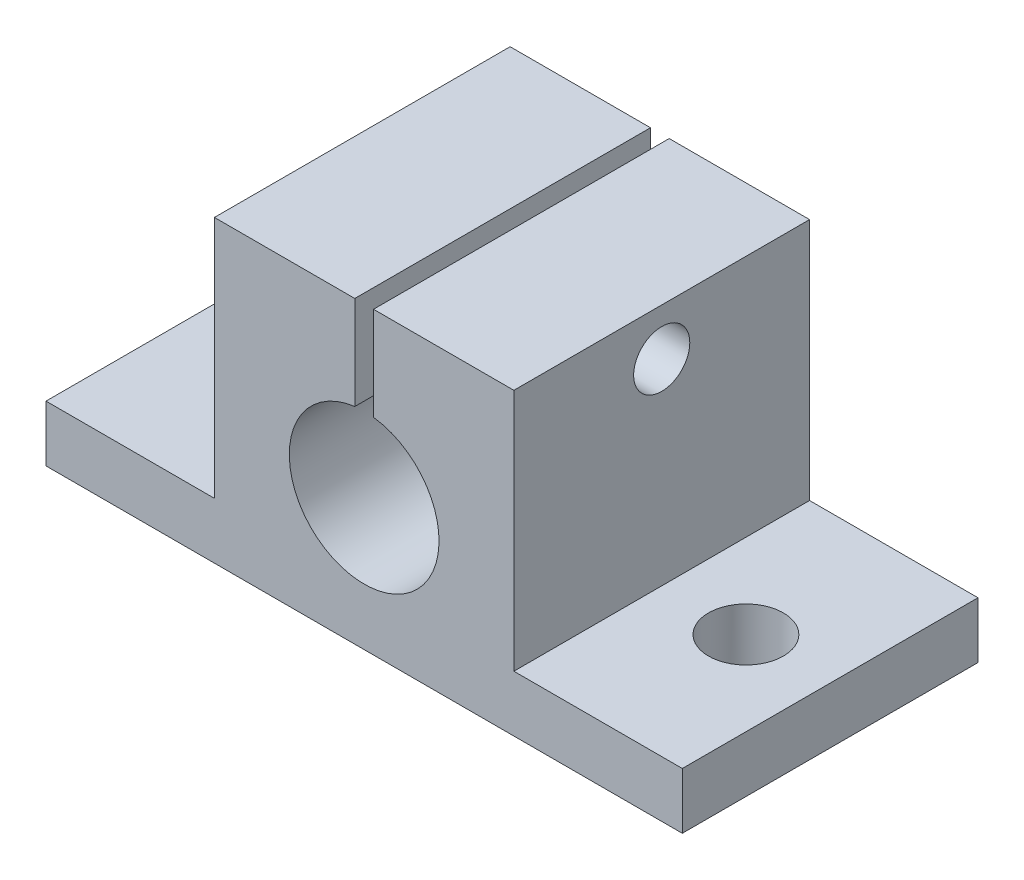
SolidWorks part; units mm, degrees
ref_plane "Front Plane" through (0, 0, 0) normal (0, 0, 1) x (1, 0, 0)
ref_plane "Top Plane" through (0, 0, 0) normal (0, 1, 0) x (1, 0, 0)
ref_plane "Right Plane" through (0, 0, 0) normal (1, 0, 0) x (0, 0, -1)
sketch "Sketch1" plane through (0, 0, 0) normal (0, 0, 1) x (1, 0, 0)
  line L0 (0, 0) -> (34, 0)
  line L1 (0, 0) -> (0, 3)
  line L2 (0, 3) -> (9, 3)
  line L3 (9, 3) -> (9, 16)
  line L4 (9, 16) -> (16.5, 16)
  line L5 (25, 16) -> (25, 3)
  line L6 (25, 3) -> (34, 3)
  line L7 (34, 3) -> (34, 0)
  line L8 (25, 16) -> (17.5, 16)
  line L9 (16.5, 16) -> (16.5, 11)
  line L10 (17.5, 16) -> (17.5, 11)
  arc A0 (17.5, 11) -> (16.5, 11) centre (17, 7.0314) cw
  point P11 (0, 0)
  point P12 (17, 0)
  point P16 (17, 3.0314)
  dimension "D8" = 4
  dimension "D10" = 5
  dimension "D1" = 34
  dimension "D2" = 3
  dimension "D3" = 13
  dimension "D4" = 7.5
  dimension "D5" = 3
  dimension "D6" = 9
  dimension "D7" = 9
  dimension "D9" = 7.5
extrude "Boss-Extrude1" add sketch "Sketch1" against normal blind 15.8
sketch "Sketch2" plane through (0, 3, 0) normal (0, 1, 0) x (1, 0, 0)
  line L0 (0, 15.8) -> (0, 0) construction
  circle A0 centre (4.5, 7.9) radius 2
  point P4 (0, 0)
  point P5 (0, 0)
  point P6 (0, 7.9)
  point P9 (0, 0)
  dimension "D1" = 4
  dimension "D2" = 4.5
extrude "Cut-Extrude1" cut sketch "Sketch2" against normal blind 15.8 contours A0
sketch "Sketch4" plane through (0, 3, 0) normal (0, 1, 0) x (1, 0, 0)
  line L0 (34, 15.8) -> (34, 0) construction
  circle A0 centre (29.5, 7.9) radius 2
  point P2 (0, 0)
  point P5 (34, 7.9)
  dimension "D1" = 4
  dimension "D2" = 4.5
extrude "Cut-Extrude2" cut sketch "Sketch4" against normal blind 15.8
sketch "Sketch5" plane through (25, 0, 0) normal (1, 0, 0) x (0, 0, -1)
  line L0 (15.8, 16) -> (0, 16) construction
  circle A0 centre (7.9, 13.5) radius 1.5
  point P4 (0, 0)
  point P7 (0, 0)
  point P8 (7.9, 16)
  dimension "D1" = 3
  dimension "D2" = 2.5
extrude "Cut-Extrude3" cut sketch "Sketch5" against normal through all
